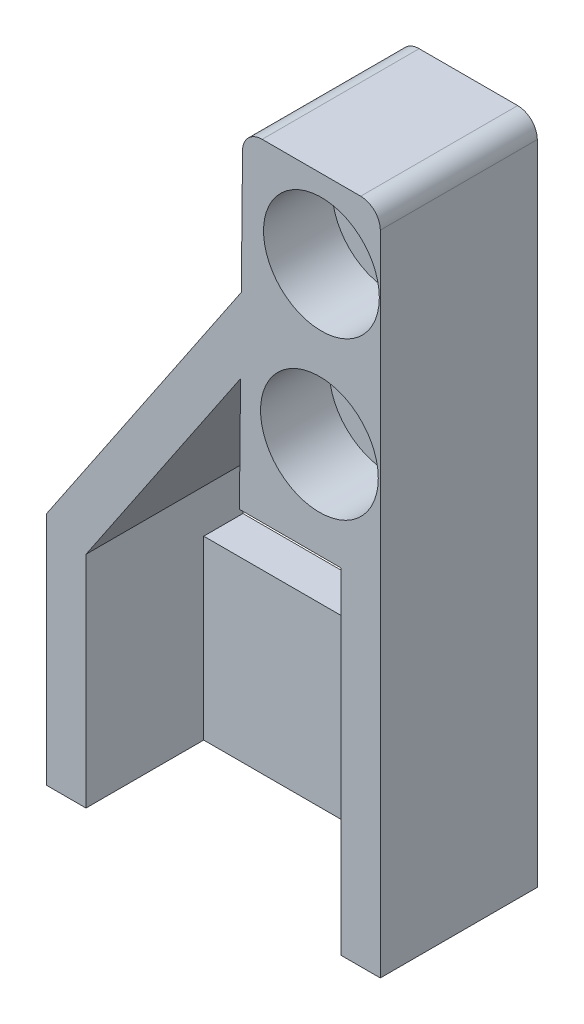
SolidWorks part; units mm, degrees
ref_plane "前视基准面" through (0, 0, 0) normal (0, 0, 1) x (1, 0, 0)
ref_plane "上视基准面" through (0, 0, 0) normal (0, 1, 0) x (1, 0, 0)
ref_plane "右视基准面" through (0, 0, 0) normal (1, 0, 0) x (0, 0, -1)
sketch "草图1" plane through (0, 0, 0) normal (0, 0, 1) x (1, 0, 0)
  line L0 (3, 25.2807) -> (3, 34.7193) construction
  line L1 (0, 0) -> (6, 0)
  line L3 (0, 34.0034) -> (-1.0106, 34.0034)
  line L4 (6, 0) -> (6, 24)
  line L5 (0, 0) -> (-11, 0)
  line L6 (-1.0106, 34.0034) -> (-1.2602, 9)
  line L7 (-1.2602, 9) -> (-11, 9)
  line L8 (-11, 0) -> (-11, 9)
  line L11 (0, 34.0034) -> (6, 34.0034)
  line L12 (6, 24) -> (6, 34.0034)
  circle A0 centre (2.8973, 22) radius 1.6
  circle A1 centre (3, 30) radius 1.6
  dimension "D5" = 3.2
  dimension "D6" = 3.2
  dimension "D3" = 17
  dimension "D4" = 9
  dimension "D7" = 22
  dimension "D8" = 8
extrude "凸台-拉伸1" add sketch "草图1" along normal blind 8
sketch "草图2" plane through (0, 0, 8) normal (0, 0, 1) x (1, 0, 0)
  line L0 (-11, 0) -> (6, 0) construction
  line L1 (-8.9982, 0) -> (4.0018, 0)
  line L2 (-8.9982, 0) -> (-8.9982, 17.0953)
  line L3 (-8.9982, 17.0953) -> (4.0018, 17.0953)
  line L4 (4.0018, 0) -> (4.0018, 17.0953)
  line L5 (-2.4982, 0) -> (-2.4982, 5.5719) construction
  dimension "D1" = 13
extrude "切除-拉伸1" cut sketch "草图2" against normal blind 6
sketch "草图3" plane through (0, 0, 8) normal (0, 0, 1) x (1, 0, 0)
  line L0 (-11, 12) -> (-1.0833, 26.7182)
  line L2 (-11, 9) -> (-8.9982, 9)
  line L3 (-11, 9) -> (-11, 12)
  line L5 (-8.9982, 9) -> (-8.9982, 11.2012)
  line L6 (-1.0833, 26.7182) -> (-1.1215, 22.8916)
  line L8 (-1.1215, 22.8916) -> (-8.9982, 11.2012)
  line L9 (-8.9982, 9) -> (-8.9982, 0) construction
  line L10 (-1.0106, 34.0034) -> (-1.1794, 17.0953) construction
extrude "凸台-拉伸2" add sketch "草图3" against normal blind 8
sketch "草图4" plane through (0, 0, 8) normal (0, 0, 1) x (1, 0, 0)
  circle A0 centre (2.8973, 22) radius 3
  circle A1 centre (3, 30) radius 2.95
  dimension "D1" = 6
  dimension "D2" = 5.9
extrude "切除-拉伸2" cut sketch "草图4" against normal blind 3.5
fillet "圆角1" radius 1 2 edges at (6, 34.0034, 4) (-1.0106, 34.0034, 4)
